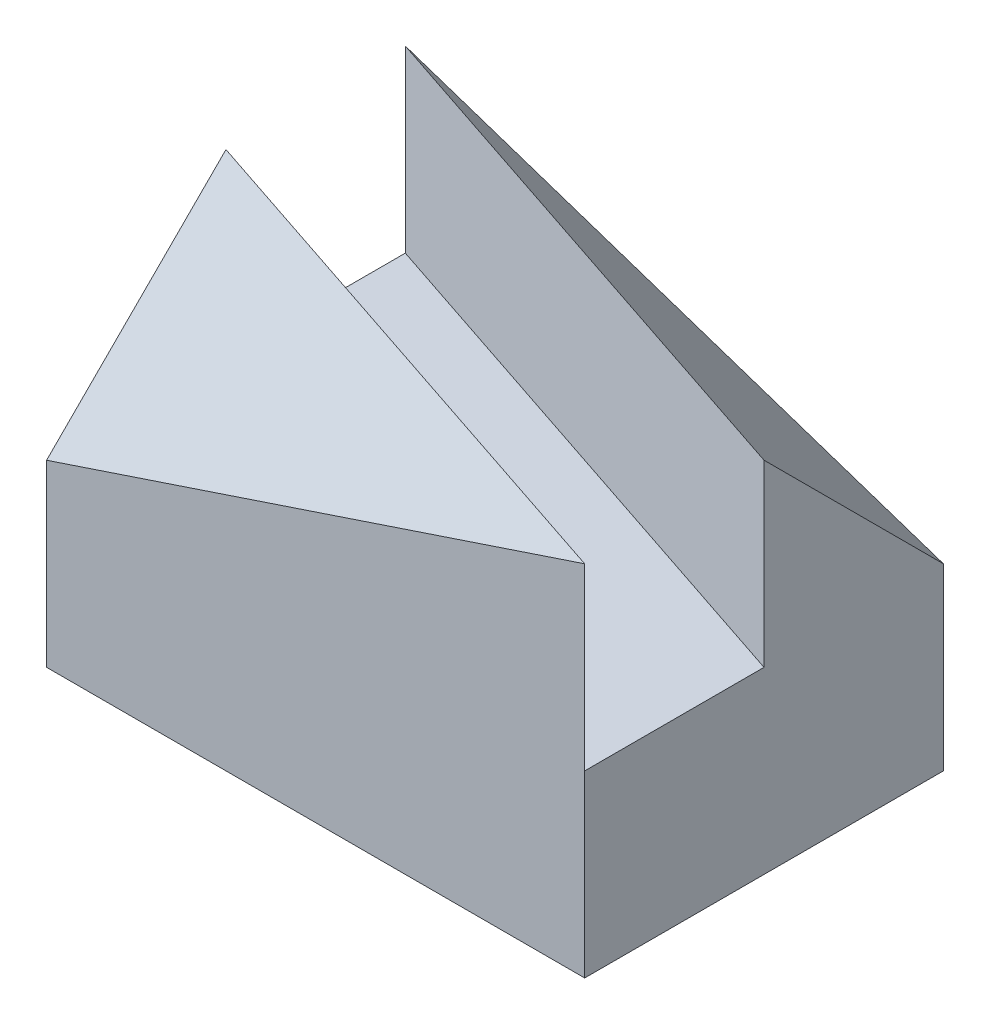
SolidWorks part; units mm, degrees
ref_plane "前基準面" through (0, 0, 0) normal (0, 0, 1) x (1, 0, 0)
ref_plane "上基準面" through (0, 0, 0) normal (0, 1, 0) x (1, 0, 0)
ref_plane "右基準面" through (0, 0, 0) normal (1, 0, 0) x (0, 0, -1)
sketch "草圖1" plane through (0, 0, 0) normal (0, 1, 0) x (1, 0, 0)
  line L0 (0, 0) -> (6, 0)
  line L1 (6, 0) -> (6, 4)
  line L2 (6, 4) -> (0, 4)
  line L3 (0, 4) -> (0, 0)
  dimension "D1" = 6
  dimension "D2" = 4
extrude "填料-伸長1" add sketch "草圖1" along normal blind 2
sketch "草圖2" plane through (0, 2, 0) normal (0, 1, 0) x (1, 0, 0)
  line L0 (0, 4) -> (6, 2)
  line L1 (6, 0) -> (6, 4) construction
  line L2 (6, 2) -> (6, 4)
  line L3 (6, 4) -> (0, 4)
extrude "填料-伸長2" add sketch "草圖2" along normal blind 2
sketch "草圖4" plane through (0, 2, 0) normal (0, 1, 0) x (1, 0, 0)
  line L0 (0, 0) -> (0, 2)
  line L1 (0, 4) -> (0, 0) construction
  line L2 (0, 2) -> (6, 0)
  line L3 (6, 0) -> (0, 0)
extrude "填料-伸長3" add sketch "草圖4" along normal blind 2
sketch3d "3D草圖1"
  line L0 (6, 2, -4) -> (6, 4, -2)
  line L1 (6, 4, -4) -> (6, 0, -4) construction
  line L2 (6, 4, -2) -> (0, 4, -4)
  line L3 (0, 4, -4) -> (6, 2, -4)
extrude "除料-伸長1" cut sketch "3D草圖1" along direction (0, -1, 0) on the side of the normal blind 2
ref_plane "平面2" through (0, 0, -4) normal (0, 0, 1) x (1, 0, 0)
sketch3d "3D草圖2"
  line L0 (0, 2, 0) -> (0, 4, -2)
  line L1 (0, 4, 0) -> (0, 0, 0) construction
  line L2 (0, 4, -2) -> (6, 4, 0)
  line L3 (6, 4, 0) -> (0, 2, 0)
extrude "除料-伸長2" cut sketch "3D草圖2" along direction (0, 0, -1) on the side of the normal blind 2
